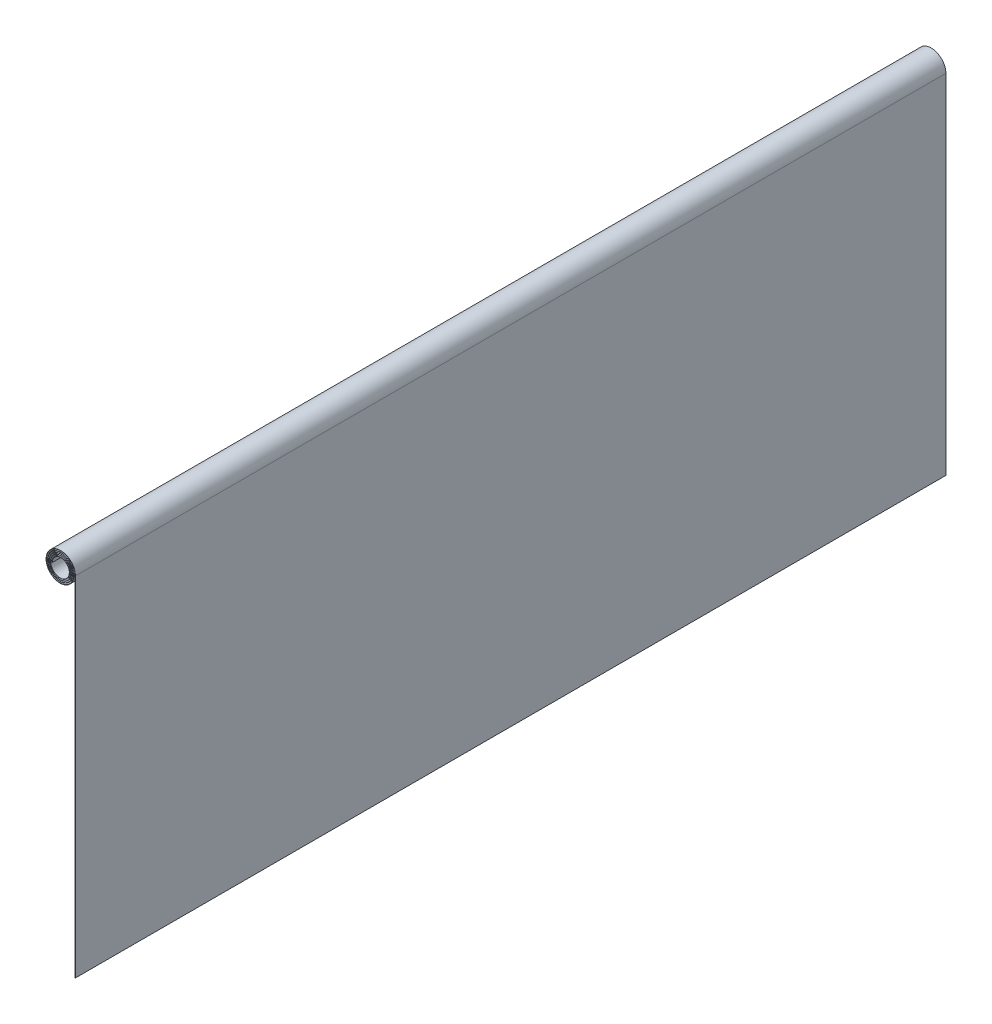
SolidWorks part; units mm, degrees
material "Q235A"
ref_plane "前视" through (0, 0, 0) normal (0, 0, 1) x (1, 0, 0)
ref_plane "上视" through (0, 0, 0) normal (0, 1, 0) x (1, 0, 0)
ref_plane "右视" through (0, 0, 0) normal (1, 0, 0) x (0, 0, -1)
sketch "草图1" plane through (0, 0, 0) normal (0, 0, 1) x (1, 0, 0)
  line L1 (25, 0) -> (25, -600)
  line L2 (50, 0) -> (-50, 0) construction
  arc A0 (15, 0) -> (-15, 0) centre (0, 0) ccw
  arc A1 (17.5, 0) -> (-17.5, 0) centre (0, 0) ccw
  arc A2 (20, 0) -> (-20, 0) centre (0, 0) ccw
  arc A3 (22.5, 0) -> (-22.5, 0) centre (0, 0) ccw
  arc A4 (25, 0) -> (-25, 0) centre (0, 0) ccw
  arc A5 (-25, 0) -> (22.5, 0) centre (-1.25, 0) ccw
  arc A6 (-22.5, 0) -> (20, 0) centre (-1.25, 0) ccw
  arc A7 (-20, 0) -> (17.5, 0) centre (-1.25, 0) ccw
  arc A8 (-17.5, 0) -> (15, 0) centre (-1.25, 0) ccw
  dimension "D1" = 30
  dimension "D2" = 35
  dimension "D3" = 40
  dimension "D4" = 45
  dimension "D5" = 50
  dimension "D6" = 600
ref_plane "基准面1" through (0, -600, 0) normal (0, 1, 0) x (1, 0, 0)
sketch "草图2" plane through (0, -600, 0) normal (0, 1, 0) x (1, 0, 0)
  line L0 (-25, 0) -> (25, 0) construction
  line L1 (24.75, -750) -> (25.25, -750)
  line L2 (24.75, -750) -> (24.75, 750)
  line L3 (24.75, 750) -> (25.25, 750)
  line L4 (25.25, -750) -> (25.25, 750)
  line L5 (24.75, -750) -> (25.25, 750) construction
  line L6 (24.75, 750) -> (25.25, -750) construction
  point P0 (25, 0)
  dimension "D1" = 1500
  dimension "D2" = 0.5
sweep "扫描1" add profiles "草图2" path "草图1"
